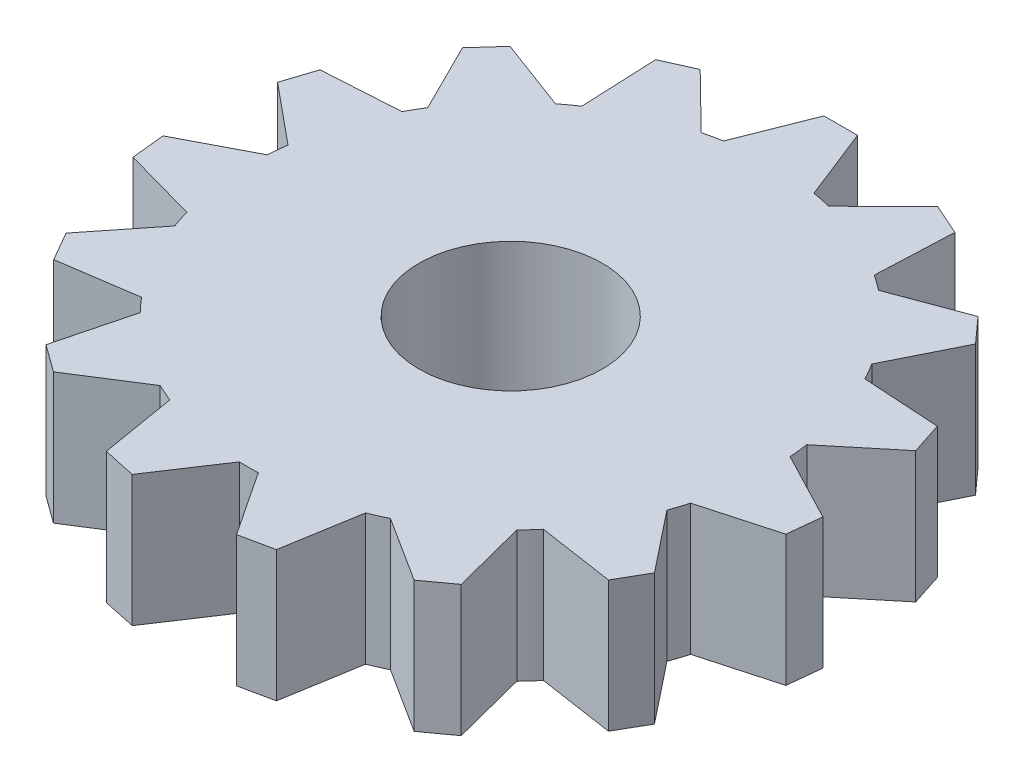
SolidWorks part; units mm, degrees
ref_plane "Alzado" through (0, 0, 0) normal (0, 0, 1) x (1, 0, 0)
ref_plane "Planta" through (0, 0, 0) normal (0, 1, 0) x (1, 0, 0)
ref_plane "Vista lateral" through (0, 0, 0) normal (1, 0, 0) x (0, 0, -1)
sketch "Croquis1" plane through (0, 0, 0) normal (0, 1, 0) x (1, 0, 0)
  line L2 (0, 15) -> (0, 13.5385) construction
  line L3 (-2.5, 15) -> (-0.964, 18.894)
  line L5 (-2.5, 15) -> (-2.5888, 14.7749)
  line L6 (2.5, 15) -> (2.5888, 14.7749)
  line L7 (2.5, 15) -> (0.964, 18.894)
  line L8 (-0.964, 18.894) -> (0.964, 18.894)
  line L9 (8.3849, 12.6863) -> (8.5656, 16.8684)
  line L10 (3.8172, 14.72) -> (6.8042, 17.6527)
  line L11 (3.8172, 14.72) -> (3.6445, 14.5505)
  line L12 (8.3849, 12.6863) -> (8.3745, 12.4446)
  line L13 (6.8042, 17.6527) -> (8.5656, 16.8684)
  line L14 (12.82, 8.1791) -> (14.6861, 11.9262)
  line L15 (9.4743, 11.8948) -> (13.3959, 13.359)
  line L16 (9.4743, 11.8948) -> (9.2477, 11.8102)
  line L17 (12.82, 8.1791) -> (12.7121, 7.9625)
  line L18 (13.3959, 13.359) -> (14.6861, 11.9262)
  line L19 (15.0384, 2.2576) -> (18.2672, 4.9217)
  line L20 (13.4933, 7.0129) -> (17.6714, 6.7554)
  line L21 (13.4933, 7.0129) -> (13.2518, 7.0278)
  line L22 (15.0384, 2.2576) -> (14.8518, 2.1036)
  line L23 (17.6714, 6.7554) -> (18.2672, 4.9217)
  line L24 (14.6565, -4.0542) -> (18.6898, -2.9337)
  line L25 (15.1791, 0.9184) -> (18.8913, -1.0162)
  line L26 (15.1791, 0.9184) -> (14.9646, 1.0302)
  line L27 (14.6565, -4.0542) -> (14.4234, -4.119)
  line L28 (18.8913, -1.0162) -> (18.6898, -2.9337)
  line L29 (11.7404, -9.6651) -> (15.8807, -10.2819)
  line L30 (14.2404, -5.3349) -> (16.8447, -8.6121)
  line L31 (14.2404, -5.3349) -> (14.0898, -5.1455)
  line L32 (11.7404, -9.6651) -> (11.5011, -9.6294)
  line L33 (16.8447, -8.6121) -> (15.8807, -10.2819)
  line L34 (6.7942, -13.6047) -> (10.3257, -15.8522)
  line L35 (10.8393, -10.6658) -> (11.8856, -14.7189)
  line L36 (10.8393, -10.6658) -> (10.7788, -10.4315)
  line L37 (6.7942, -13.6047) -> (6.5901, -13.4748)
  line L38 (11.8856, -14.7189) -> (10.3257, -15.8522)
  line L39 (0.6733, -15.192) -> (2.9853, -18.6816)
  line L40 (5.564, -14.1524) -> (4.8713, -18.2807)
  line L41 (5.564, -14.1524) -> (5.6041, -13.9138)
  line L42 (0.6733, -15.192) -> (0.5397, -14.9903)
  line L43 (4.8713, -18.2807) -> (2.9853, -18.6816)
  line L44 (-5.564, -14.1524) -> (-4.8713, -18.2807)
  line L45 (-0.6733, -15.192) -> (-2.9853, -18.6816)
  line L46 (-0.6733, -15.192) -> (-0.5397, -14.9903)
  line L47 (-5.564, -14.1524) -> (-5.6041, -13.9138)
  line L48 (-2.9853, -18.6816) -> (-4.8713, -18.2807)
  line L49 (-10.8393, -10.6658) -> (-11.8856, -14.7189)
  line L50 (-6.7942, -13.6047) -> (-10.3257, -15.8522)
  line L51 (-6.7942, -13.6047) -> (-6.5901, -13.4748)
  line L52 (-10.8393, -10.6658) -> (-10.7788, -10.4315)
  line L53 (-10.3257, -15.8522) -> (-11.8856, -14.7189)
  line L54 (-14.2404, -5.3349) -> (-16.8447, -8.6121)
  line L55 (-11.7404, -9.6651) -> (-15.8807, -10.2819)
  line L56 (-11.7404, -9.6651) -> (-11.5011, -9.6294)
  line L57 (-14.2404, -5.3349) -> (-14.0898, -5.1455)
  line L58 (-15.8807, -10.2819) -> (-16.8447, -8.6121)
  line L59 (-15.1791, 0.9184) -> (-18.8913, -1.0162)
  line L60 (-14.6565, -4.0542) -> (-18.6898, -2.9337)
  line L61 (-14.6565, -4.0542) -> (-14.4234, -4.119)
  line L62 (-15.1791, 0.9184) -> (-14.9646, 1.0302)
  line L63 (-18.6898, -2.9337) -> (-18.8913, -1.0162)
  line L64 (-13.4933, 7.0129) -> (-17.6714, 6.7554)
  line L65 (-15.0384, 2.2576) -> (-18.2672, 4.9217)
  line L66 (-15.0384, 2.2576) -> (-14.8518, 2.1036)
  line L67 (-13.4933, 7.0129) -> (-13.2518, 7.0278)
  line L68 (-18.2672, 4.9217) -> (-17.6714, 6.7554)
  line L69 (-9.4743, 11.8948) -> (-13.3959, 13.359)
  line L70 (-12.82, 8.1791) -> (-14.6861, 11.9262)
  line L71 (-12.82, 8.1791) -> (-12.7121, 7.9625)
  line L72 (-9.4743, 11.8948) -> (-9.2477, 11.8102)
  line L73 (-14.6861, 11.9262) -> (-13.3959, 13.359)
  line L74 (-3.8172, 14.72) -> (-6.8042, 17.6527)
  line L75 (-8.3849, 12.6863) -> (-8.5656, 16.8684)
  line L76 (-8.3849, 12.6863) -> (-8.3745, 12.4446)
  line L77 (-3.8172, 14.72) -> (-3.6445, 14.5505)
  line L78 (-8.5656, 16.8684) -> (-6.8042, 17.6527)
  circle A0 centre (0, 0) radius 5.25
  arc A2 (-2.5888, 14.7749) -> (-3.6445, 14.5505) centre (0, 0) ccw
  arc A3 (-8.3745, 12.4446) -> (-9.2477, 11.8102) centre (0, 0) ccw
  arc A4 (-12.7121, 7.9625) -> (-13.2518, 7.0278) centre (0, 0) ccw
  arc A5 (-14.8518, 2.1036) -> (-14.9646, 1.0302) centre (0, 0) ccw
  arc A6 (-14.4234, -4.119) -> (-14.0898, -5.1455) centre (0, 0) ccw
  arc A7 (-11.5011, -9.6294) -> (-10.7788, -10.4315) centre (0, 0) ccw
  arc A8 (-6.5901, -13.4748) -> (-5.6041, -13.9138) centre (0, 0) ccw
  arc A9 (-0.5397, -14.9903) -> (0.5397, -14.9903) centre (0, 0) ccw
  arc A10 (5.6041, -13.9138) -> (6.5901, -13.4748) centre (0, 0) ccw
  arc A11 (10.7788, -10.4315) -> (11.5011, -9.6294) centre (0, 0) ccw
  arc A12 (14.0898, -5.1455) -> (14.4234, -4.119) centre (0, 0) ccw
  arc A13 (14.9646, 1.0302) -> (14.8518, 2.1036) centre (0, 0) ccw
  arc A14 (13.2518, 7.0278) -> (12.7121, 7.9625) centre (0, 0) ccw
  arc A15 (9.2477, 11.8102) -> (8.3745, 12.4446) centre (0, 0) ccw
  arc A16 (3.6445, 14.5505) -> (2.5888, 14.7749) centre (0, 0) ccw
  point P6 (0, 5.25)
  point P8 (0, 15)
  point P99 (0, 0)
  dimension "D1" = 10.5
  dimension "D2" = 30
  dimension "D3" = 5
  dimension "D4" = 15
extrude "Saliente-Extruir1" add sketch "Croquis1" along normal blind 7.5
